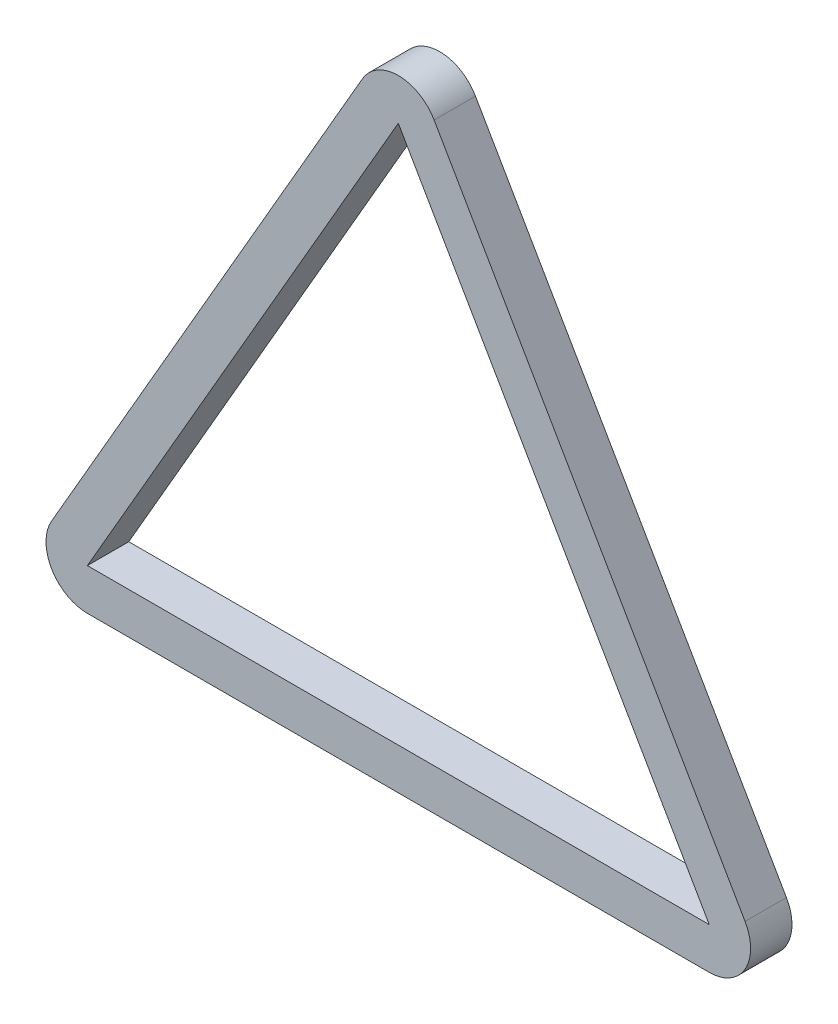
SolidWorks part; units mm, degrees
ref_plane "前基準面" through (0, 0, 0) normal (0, 0, 1) x (1, 0, 0)
ref_plane "上基準面" through (0, 0, 0) normal (0, 1, 0) x (1, 0, 0)
ref_plane "右基準面" through (0, 0, 0) normal (1, 0, 0) x (0, 0, -1)
sketch "草圖1" plane through (0, 0, 0) normal (0, 0, 1) x (1, 0, 0)
  line L0 (0, 179.4831) -> (-185, -140.9463)
  line L1 (-185, -140.9463) -> (185, -140.9463)
  line L2 (185, -140.9463) -> (0, 179.4831)
  line L3 (0, 139.4831) -> (-150.359, -120.9463)
  line L4 (-150.359, -120.9463) -> (150.359, -120.9463)
  line L5 (150.359, -120.9463) -> (0, 139.4831)
  point P4 (0, -140.9463)
  dimension "D1" = 370
  dimension "D2" = 370
  dimension "D3" = 370
  dimension "D4" = 20
extrude "填料-伸長1" add sketch "草圖1" along normal blind 20
fillet "圓角1" radius 20 3 edges at (0, 179.4831, 10) (185, -140.9463, 10) (-185, -140.9463, 10)
sketch "草圖2" plane through (0, 0, 20) normal (0, 0, 1) x (1, 0, 0)
  line L0 (92.5, 19.2684) -> (-167.6795, -130.9463) construction
  line L1 (167.6795, -110.9463) -> (17.3205, 149.4831) construction
  line L2 (0, -140.9463) -> (0, 159.4831) construction
  line L3 (-150.359, -140.9463) -> (150.359, -140.9463) construction
  line L4 (167.6795, -130.9463) -> (-92.5, 19.2684) construction
  line L5 (-17.3205, 149.4831) -> (-167.6795, -110.9463) construction
  line L6 (124.75, -36.5903) -> (107.4295, -46.5903) construction
  line L7 (150.359, -120.9463) -> (0, 139.4831) construction
  line L8 (60.25, 75.127) -> (42.9295, 65.127) construction
  line L9 (-60.25, 75.127) -> (-42.9295, 65.127) construction
  line L10 (-124.75, -36.5903) -> (-107.4295, -46.5903) construction
  line L11 (-64.5, -140.9463) -> (-64.5, -120.9463) construction
  line L12 (64.5, -140.9463) -> (64.5, -120.9463) construction
  arc A0 (-167.6795, -110.9463) -> (-150.359, -140.9463) centre (-150.359, -120.9463) ccw construction
  arc A1 (17.3205, 149.4831) -> (-17.3205, 149.4831) centre (0, 139.4831) ccw construction
  arc A2 (150.359, -140.9463) -> (167.6795, -110.9463) centre (150.359, -120.9463) ccw construction
  dimension "D1" = 64.5
